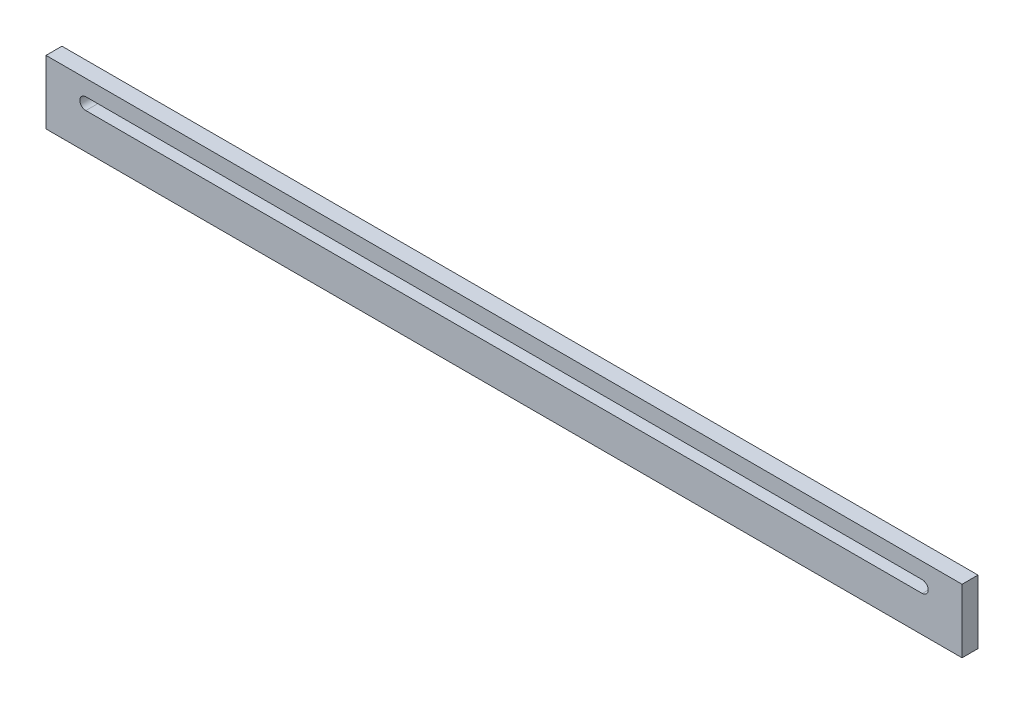
SolidWorks part; units mm, degrees
ref_plane "前视基准面" through (0, 0, 0) normal (0, 0, 1) x (1, 0, 0)
ref_plane "上视基准面" through (0, 0, 0) normal (0, 1, 0) x (1, 0, 0)
ref_plane "右视基准面" through (0, 0, 0) normal (1, 0, 0) x (0, 0, -1)
sketch "草图1" plane through (0, 0, 0) normal (0, 0, 1) x (1, 0, 0)
  line L0 (10, -5.5) -> (220, -5.5) construction
  line L1 (0, 0) -> (230, 0)
  line L2 (0, 0) -> (0, -16)
  line L3 (0, -16) -> (230, -16)
  line L4 (230, 0) -> (230, -16)
  line L5 (10, -4) -> (220, -4)
  line L6 (10, -7) -> (220, -7)
  arc A0 (10, -4) -> (10, -7) centre (10, -5.5) ccw
  arc A1 (220, -7) -> (220, -4) centre (220, -5.5) ccw
  point P7 (115, -5.5)
  dimension "D5" = 1.5
  dimension "D1" = 230
  dimension "D2" = 16
  dimension "D3" = 10
  dimension "D4" = 10
  dimension "D6" = 12
extrude "凸台-拉伸1" add sketch "草图1" along normal blind 4
